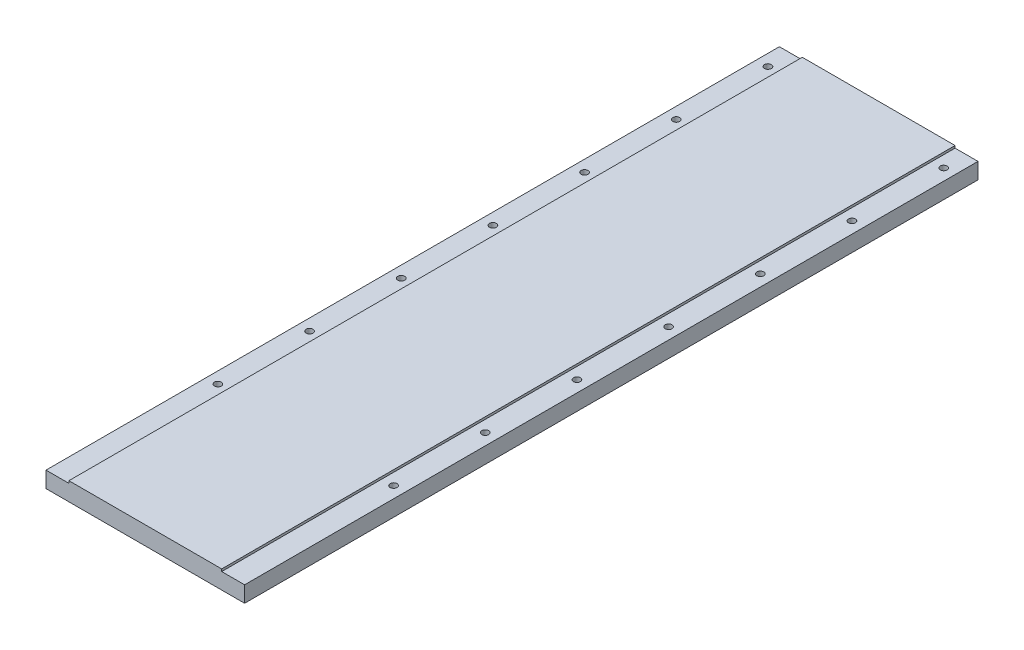
SolidWorks part; units mm, degrees
material "Liga 6061"
ref_plane "Plano frontal" through (0, 0, 0) normal (0, 0, 1) x (1, 0, 0)
ref_plane "Plano superior" through (0, 0, 0) normal (0, 1, 0) x (1, 0, 0)
ref_plane "Plano direito" through (0, 0, 0) normal (1, 0, 0) x (0, 0, -1)
sketch "Sketch1" plane through (0, 0, 0) normal (0, 0, 1) x (1, 0, 0)
  line L0 (-65, 0) -> (65, 0)
  line L1 (65, 0) -> (65, 10.5)
  line L2 (65, 10.5) -> (50, 10.5)
  line L3 (50, 10.5) -> (50, 12)
  line L4 (50, 12) -> (-50, 12)
  line L5 (-50, 12) -> (-50, 10.5)
  line L6 (-50, 10.5) -> (-65, 10.5)
  line L7 (-65, 10.5) -> (-65, 0)
  line L8 (0, 0) -> (0, 12) construction
  point P4 (0, 0)
  dimension "D1" = 130
  dimension "D2" = 1.5
  dimension "D3" = 12
  dimension "D4" = 15
extrude "Boss-Extrude1" add sketch "Sketch1" along normal blind 480
hole_wizard "M4 Clearance Hole1" positions "Sketch2" profile "Sketch3" hole size "M4" standard "JIS" end condition through all
sketch "Sketch2" plane through (14.8504, 10.5, 240) normal (0, 1, 0) x (1, 0, 0)
  point P0 (-72.3504, -135)
  point P1 (-72.3504, 225)
  point P2 (-72.3504, -75)
  point P3 (-72.3504, -15)
  point P4 (-72.3504, 45)
  point P5 (-72.3504, 105)
  point P6 (-72.3504, 165)
  point P7 (-72.3504, 225)
sketch "Sketch3" plane through (-57.5, 10.5, 375) normal (1, 0, 0) x (0, 0, 1)
  line L0 (0, 0) -> (0, 10.5)
  line L1 (0, 10.5) -> (2.25, 10.5)
  line L2 (2.25, 10.5) -> (2.25, 0)
  line L3 (2.25, 0) -> (0, 0)
  line L4 (0, -6.35) -> (0, 107.95) construction
  dimension "Thru Hole Dia." = 4.5
  dimension "Thru Hole Depth" = 10.5
hole_wizard "M4 Clearance Hole2" positions "Sketch4" profile "Sketch5" hole size "M4" standard "JIS" end condition through all
sketch "Sketch4" plane through (14.8504, 10.5, 240) normal (0, 1, 0) x (1, 0, 0)
  point P0 (42.6496, -135)
  point P1 (42.6496, 225)
  point P2 (42.6496, -75)
  point P3 (42.6496, -15)
  point P4 (42.6496, 45)
  point P5 (42.6496, 105)
  point P6 (42.6496, 165)
  point P7 (42.6496, 225)
sketch "Sketch5" plane through (57.5, 10.5, 375) normal (1, 0, 0) x (0, 0, 1)
  line L0 (0, 0) -> (0, 10.5)
  line L1 (0, 10.5) -> (2.25, 10.5)
  line L2 (2.25, 10.5) -> (2.25, 0)
  line L3 (2.25, 0) -> (0, 0)
  line L4 (0, -6.35) -> (0, 107.95) construction
  dimension "Thru Hole Dia." = 4.5
  dimension "Thru Hole Depth" = 10.5
